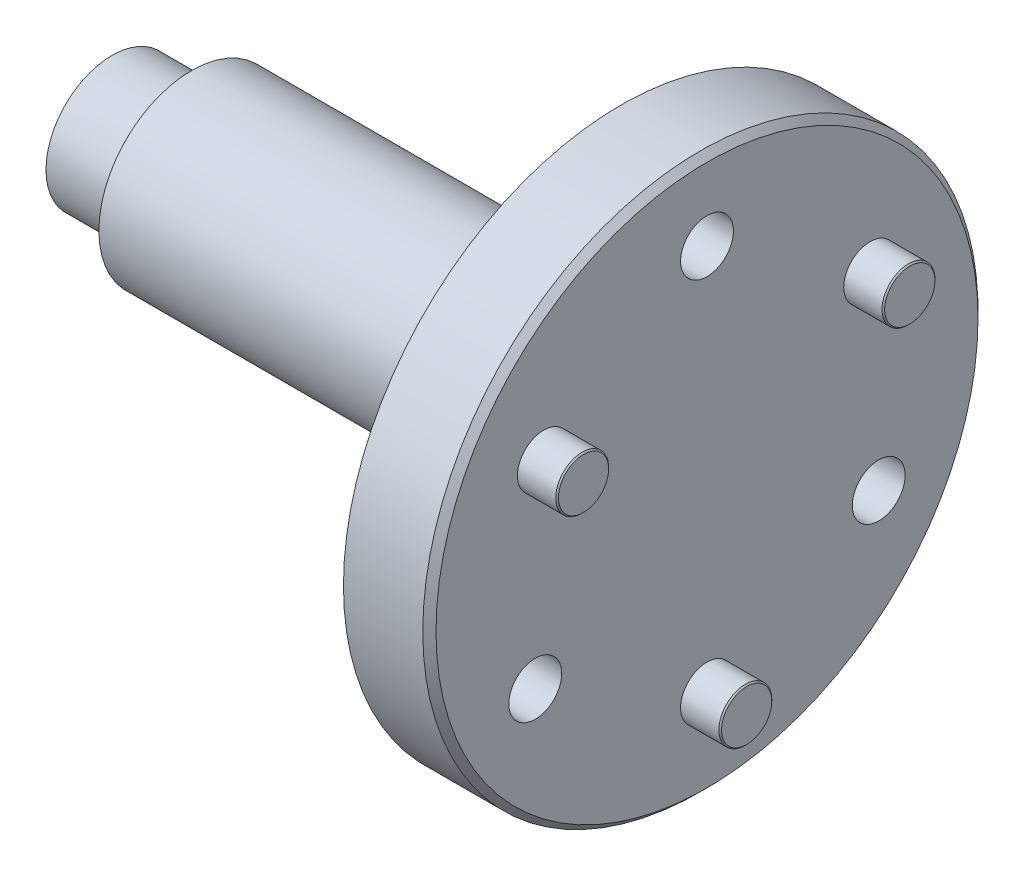
SolidWorks part; units mm, degrees
ref_plane "Front Plane" through (0, 0, 0) normal (0, 0, 1) x (1, 0, 0)
ref_plane "Top Plane" through (0, 0, 0) normal (0, 1, 0) x (1, 0, 0)
ref_plane "Right Plane" through (0, 0, 0) normal (1, 0, 0) x (0, 0, -1)
sketch "Sketch1" plane through (0, 0, 0) normal (0, 0, 1) x (1, 0, 0)
  line L0 (-22.25, 0) -> (-22.25, 5)
  line L1 (55, 0) -> (-55, 0) construction
  line L2 (-22.25, 5) -> (-16.25, 5)
  line L3 (-16.25, 5) -> (-16.25, 7)
  line L4 (-16.25, 7) -> (16.25, 7)
  line L5 (16.25, 7) -> (16.25, 21)
  line L6 (16.25, 21) -> (22.75, 21)
  line L7 (22.75, 21) -> (22.75, 0)
  line L8 (22.75, 0) -> (-22.25, 0)
  line L9 (-54.0782, 0) -> (43.783, 0) construction
  line L10 (0, -44.7868) -> (0, 44.7868) construction
  dimension "D1" = 6
  dimension "D2" = 6.5
  dimension "D3" = 32.5
  dimension "D4" = 16.25
  dimension "D5" = 5
  dimension "D6" = 21
  dimension "D7" = 7
revolve "Revolve1" add sketch "Sketch1" angle 360 about L9
chamfer "Chamfer1" distance 0.5 angle 45 1 edges at (22.75, 0, 21)
sketch "Sketch2" plane through (22.75, 0, 0) normal (1, 0, 0) x (0, 0, -1)
  line L0 (0, 44.2539) -> (0, -44.2539) construction
  circle A0 centre (0, 15) radius 2
  dimension "D1" = 15
  dimension "D2" = 4
extrude "Cut-Extrude1" cut sketch "Sketch2" against normal up to surface (6.5 mm away) up to face at (16.25, 0, 7)
pattern_circular "CirPattern1" count 3 over 360 about axis through (0, 0, 0) along (1, 0, 0) of "Cut-Extrude1"
sketch "Sketch3" plane through (22.75, 0, 0) normal (1, 0, 0) x (0, 0, -1)
  line L0 (0, 0) -> (12.3409, 7.125) construction
  line L2 (0, 44.2539) -> (0, -44.2539) construction
  circle A0 centre (12.3409, 7.125) radius 2
  dimension "D1" = 14.25
  dimension "D3" = 4
  dimension "D2" = 60
extrude "Boss-Extrude1" add sketch "Sketch3" along normal blind 3
chamfer "Chamfer2" distance 0.1 angle 45 1 edges at (25.75, 7.125, -14.3409)
pattern_circular "CirPattern3" count 3 over 360 about axis through (0, 0, 0) along (1, 0, 0) of "Chamfer2", "Boss-Extrude1"
